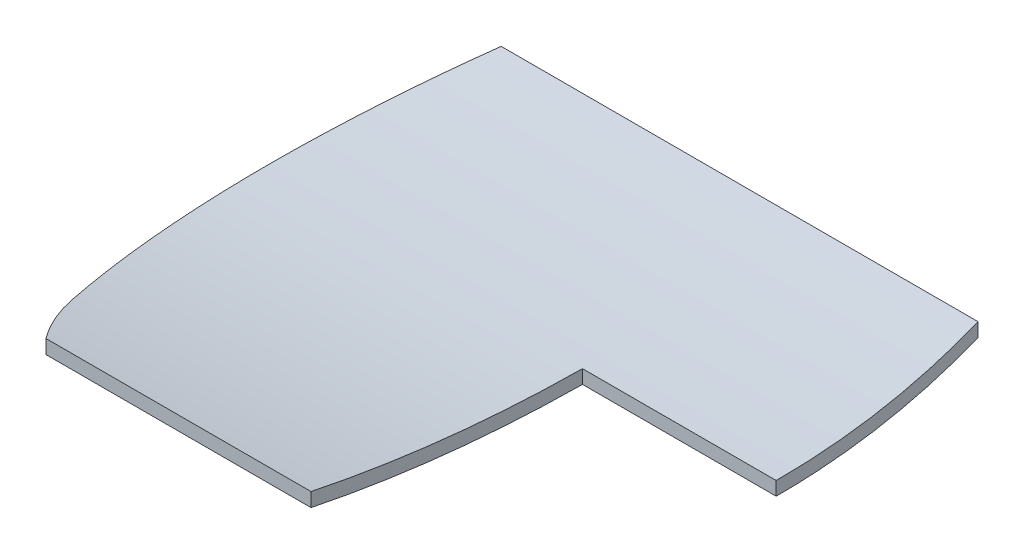
SolidWorks part; units mm, degrees
ref_plane "Front Plane" through (0, 0, 0) normal (0, 0, 1) x (1, 0, 0)
ref_plane "Top Plane" through (0, 0, 0) normal (0, 1, 0) x (1, 0, 0)
ref_plane "Right Plane" through (0, 0, 0) normal (1, 0, 0) x (0, 0, -1)
sketch "Sketch1" plane through (0, 0, 0) normal (0, 1, 0) x (1, 0, 0)
  line L0 (-75.8377, 3.6332) -> (4.1623, 3.6332)
  line L1 (-75.8377, 3.6332) -> (-75.8377, -71.3668)
  line L2 (4.1623, 3.6332) -> (4.1623, -71.3668)
  line L3 (-75.8377, -71.3668) -> (4.1623, -71.3668)
  dimension "D1" = 80
  dimension "D2" = 75
extrude "Boss-Extrude1" add sketch "Sketch1" along normal blind 30
sketch "Sketch6" plane through (0, 30, 0) normal (0, 1, 0) x (1, 0, 0)
  line L0 (-71.3758, 3.6332) -> (-108.8208, 13.4215)
  line L1 (4.1623, 3.6332) -> (-75.8377, 3.6332) construction
  line L2 (4.1623, -71.3668) -> (4.1623, 3.6332) construction
  line L3 (-108.8208, 13.4215) -> (-125.5846, -100.3701)
  line L4 (-125.5846, -100.3701) -> (-10.92, -107.6689)
  line L5 (-10.92, -107.6689) -> (16.0422, -75.5319)
  line L6 (16.0422, -75.5319) -> (16.0422, -32.2472)
  line L7 (-75.8377, -71.3668) -> (4.1623, -71.3668) construction
  line L8 (-65.4038, -71.3668) -> (-25.2117, -71.3668)
  line L9 (-75.8377, 3.6332) -> (-75.8377, -71.3668) construction
  line L10 (4.1623, -30.1991) -> (-25.2117, -30.1991)
  line L11 (0.9341, 3.6332) -> (13.1704, 8.0963)
  line L12 (-25.2117, -30.1991) -> (-25.2117, -71.3668)
  line L13 (16.0422, -32.2472) -> (13.1704, 8.0963)
  arc A0 (-71.3758, 3.6332) -> (-70.1117, -62.7591) centre (35.3142, -27.5436) ccw
  arc A1 (0.9341, 3.6332) -> (4.1623, -30.1991) centre (-192.8822, -31.9303) cw
  arc A2 (-70.1117, -62.7591) -> (-65.4038, -71.3668) centre (-43.8504, -53.987) ccw
extrude "Cut-Extrude3" cut sketch "Sketch6" against normal blind 30
sketch "Sketch7" plane through (-25.2117, 0, 0) normal (1, 0, 0) x (0, 0, -1)
  line L0 (3.6332, 4.4122) -> (25.8665, 63.3946)
  line L1 (25.8665, 63.3946) -> (-68.1872, 84.3344)
  line L2 (-68.1872, 84.3344) -> (-84.6994, 46.8544)
  line L3 (-84.6994, 46.8544) -> (-91.1693, 32.1689)
  line L4 (3.6332, 0) -> (3.6332, 30) construction
  line L5 (-71.3668, 0) -> (-71.3668, 30) construction
  line L6 (-71.3668, 6.5258) -> (-77.9148, 5.87)
  line L7 (-77.9148, 5.87) -> (-71.3668, 4.4122)
  line L8 (-30.1991, 0) -> (-71.3668, 0) construction
  line L9 (3.6332, 2.3195) -> (10.4873, -37.0612)
  line L10 (10.4873, -37.0612) -> (-79.8999, -15.4783)
  line L11 (-79.8999, -15.4783) -> (-91.1693, 32.1689)
  arc A3 (-71.3668, 4.4122) -> (3.6332, 2.3195) centre (-27.9344, 215.976) ccw
  arc A4 (3.6332, 4.4122) -> (-71.3668, 6.5258) centre (-27.9344, 215.976) cw
  point P2 (3.6332, 4.4122)
  dimension "D1" = 215.976
extrude "Cut-Extrude4" cut sketch "Sketch7" against normal blind 53 and the other way blind 46
